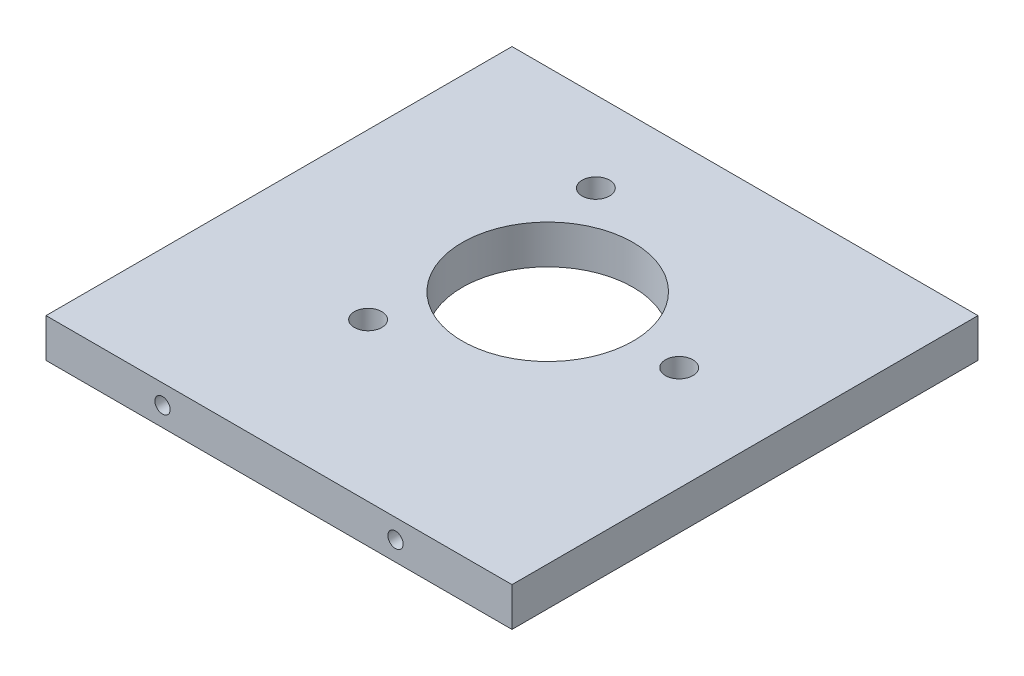
SolidWorks part; units mm, degrees
ref_plane "Front Plane" through (0, 0, 0) normal (0, 0, 1) x (1, 0, 0)
ref_plane "Top Plane" through (0, 0, 0) normal (0, 1, 0) x (1, 0, 0)
ref_plane "Right Plane" through (0, 0, 0) normal (1, 0, 0) x (0, 0, -1)
sketch "Sketch1" plane through (0, 0, 0) normal (0, 0, 1) x (1, 0, 0)
  line L0 (0, 3.175) -> (0, -3.175)
  line L1 (-38.1, 0) -> (38.1, 0) construction
  point P6 (0, 0)
  dimension "Width" = 76.2
  dimension "Thk" = 6.35
sketch "Sketch2" plane through (0, 0, 0) normal (1, 0, 0) x (0, 0, -1)
  line L0 (76.2, 0) -> (-76.2, 0)
  point P4 (0, 0)
  dimension "Length" = 152.4
sketch "Sketch3" plane through (0, 0, 0) normal (0, 0, 1) x (1, 0, 0)
  line L1 (38.1, 3.175) -> (-38.1, 3.175)
  line L2 (38.1, 3.175) -> (38.1, -3.175)
  line L3 (38.1, -3.175) -> (-38.1, -3.175)
  line L4 (-38.1, 3.175) -> (-38.1, -3.175)
  line L5 (38.1, 3.175) -> (-38.1, -3.175) construction
  line L6 (38.1, -3.175) -> (-38.1, 3.175) construction
  point P0 (0, 0)
extrude "Boss-Extrude1" add sketch "Sketch3" along normal up to vertex (76.2 mm away) and the other way up to vertex (76.2 mm away) up to point (0, 0, 76.2) other way up to point (0, 0, -76.2)
sketch "Sketch4" plane through (0, 3.175, 0) normal (0, 1, 0) x (1, 0, 0)
  point P1 (0, -1.15)
hole_wizard "M8 Clearance Hole1" [suppressed] positions "Sketch5" profile "Sketch6" hole size "M8" standard "ANSI Metric"
sketch "Sketch5" plane through (0, 3.175, 0) normal (0, 1, 0) x (1, 0, 0)
  point P8 (0, -1.15)
sketch "Sketch6" plane through (0, 3.175, 1.15) normal (1, 0, 0) x (0, 0, 1)
  line L0 (0, 0) -> (0, 6.35)
  line L1 (0, 6.35) -> (4.5, 6.35)
  line L2 (4.5, 6.35) -> (4.5, 0)
  line L5 (4.5, 0) -> (0, 0)
  line L11 (0, -6.35) -> (0, 107.95) construction
  dimension "Thru Hole Dia." = 9
  dimension "Thru Hole Depth" = 6.35
sketch "Sketch7" plane through (0, 3.175, 0) normal (0, 1, 0) x (1, 0, 0)
  point P0 (-8.2489, -5.9125)
  point P1 (0, -10.675)
  point P3 (8.2489, -5.9125)
  point P5 (8.2489, 3.6125)
  point P7 (0, 8.375)
  point P9 (-8.2489, 3.6125)
hole_wizard "CSK for M3 Flat Head Machine Screw1" [suppressed] positions "Sketch8" profile "Sketch10" countersink size "M3" standard "ANSI Metric"
sketch "Sketch8" plane through (0, 3.175, 0) normal (0, 1, 0) x (1, 0, 0)
  point P0 (-8.2489, -5.9125)
  point P3 (0, -10.675)
  point P6 (8.2489, -5.9125)
  point P9 (8.2489, 3.6125)
  point P12 (0, 8.375)
  point P15 (-8.2489, 3.6125)
sketch "Sketch10" plane through (-8.2489, -3.175, 5.9125) normal (1, 0, 0) x (0, 0, -1)
  line L0 (0, 0) -> (0, 6.35)
  line L1 (0, 6.35) -> (1.7, 6.35)
  line L2 (1.7, 6.35) -> (1.7, 1.45)
  line L3 (1.7, 1.45) -> (3.15, 0)
  line L5 (3.15, 0) -> (0, 0)
  line L6 (-1.7, 1.45) -> (-3.15, 0) construction
  line L11 (0, -6.35) -> (0, 107.95) construction
  dimension "Thru Hole Dia." = 3.4
  dimension "Thru Hole Depth" = 6.35
  dimension "Near C'Sink Dia." = 6.3
  dimension "Near C'Sink Angle" = 90
sketch "Sketch11" plane through (0, -3.175, 0) normal (0, -1, 0) x (1, 0, 0)
  circle A0 centre (-0.451, 31.8101) radius 13.97
  point P0 (-0.451, 31.8101)
  dimension "D1" = 27.94
extrude "Cut-Extrude1" cut sketch "Sketch11" against normal through all
sketch "Sketch12" plane through (0, -3.175, 0) normal (0, -1, 0) x (1, 0, 0)
  point P0 (-11.201, 13.1905)
  point P1 (21.049, 31.8101)
  point P3 (-11.201, 50.4296)
hole_wizard "CSK for M4 Flat Head Machine Screw1" positions "Sketch13" profile "Sketch14" countersink size "M4" standard "ANSI Metric" end condition through all
sketch "Sketch13" plane through (0, -3.175, 0) normal (0, -1, 0) x (-1, 0, 0)
  point P0 (11.201, -13.1905)
  point P3 (-21.049, -31.8101)
  point P6 (11.201, -50.4296)
sketch "Sketch14" plane through (-11.201, -3.175, 13.1905) normal (1, 0, 0) x (0, 0, -1)
  line L0 (0, 0) -> (0, 6.35)
  line L1 (0, 6.35) -> (2.25, 6.35)
  line L2 (2.25, 6.35) -> (2.25, 2.45)
  line L3 (2.25, 2.45) -> (4.7, 0)
  line L5 (4.7, 0) -> (0, 0)
  line L6 (-2.25, 2.45) -> (-4.7, 0) construction
  line L11 (0, -6.35) -> (0, 107.95) construction
  dimension "Thru Hole Dia." = 4.5
  dimension "Thru Hole Depth" = 6.35
  dimension "Near C'Sink Dia." = 9.4
  dimension "Near C'Sink Angle" = 90
sketch "Sketch15" plane through (0, -3.175, 0) normal (0, -1, 0) x (1, 0, 0)
  point P0 (-0.451, 31.8101)
hole_wizard "M16 Clearance Hole1" [suppressed] positions "Sketch18" profile "Sketch19" hole size "M16" standard "ANSI Metric"
sketch "Sketch18" plane through (0, -3.175, 0) normal (0, -1, 0) x (-1, 0, 0)
  point P0 (4.1552, -31.8101)
sketch "Sketch19" plane through (-4.1552, -3.175, 31.8101) normal (1, 0, 0) x (0, 0, -1)
  line L0 (0, 0) -> (0, 6.35)
  line L1 (0, 6.35) -> (8.75, 6.35)
  line L2 (8.75, 6.35) -> (8.75, 0)
  line L5 (8.75, 0) -> (0, 0)
  line L11 (0, -6.35) -> (0, 107.95) construction
  dimension "Thru Hole Dia." = 17.5
  dimension "Thru Hole Depth" = 6.35
sketch "Sketch20" plane through (0, -3.175, 0) normal (0, -1, 0) x (1, 0, 0)
  line L0 (-38.1, 76.2) -> (-38.1, -76.2) construction
  line L1 (38.1, -76.2) -> (-38.1, -76.2)
  line L2 (38.1, -76.2) -> (38.1, 0)
  line L3 (38.1, 0) -> (-38.1, 0)
  line L4 (-38.1, -76.2) -> (-38.1, 0)
  line L5 (-38.1, 76.2) -> (38.1, 76.2) construction
  dimension "D1" = 76.2
extrude "Cut-Extrude2" cut sketch "Sketch20" against normal through all
sketch "Sketch21" plane through (0, 3.175, 0) normal (0, 1, 0) x (1, 0, 0)
  circle A0 centre (0.6258, -38.1) radius 13.97
  point P0 (0.6258, -38.1)
  dimension "D1" = 27.94
extrude "Cut-Extrude3" [suppressed] cut sketch "Sketch21" against normal through all
sketch "Sketch22" plane through (0, 3.175, 0) normal (0, 1, 0) x (1, 0, 0)
  point P0 (0.6258, -59.6)
  point P1 (-17.9937, -27.35)
  point P3 (19.2454, -27.35)
hole_wizard "CSK for M4 Flat Head Machine Screw2" [suppressed] positions "Sketch23" profile "Sketch25" countersink size "M4" standard "ANSI Metric"
sketch "Sketch23" plane through (0, 3.175, 0) normal (0, 1, 0) x (1, 0, 0)
  point P0 (0.6258, -59.6)
  point P3 (19.2454, -27.35)
  point P6 (-17.9937, -27.35)
sketch "Sketch25" plane through (0.6258, 3.175, 59.6) normal (1, 0, 0) x (0, 0, 1)
  line L0 (0, 0) -> (0, 6.35)
  line L1 (0, 6.35) -> (2.25, 6.35)
  line L2 (2.25, 6.35) -> (2.25, 2.45)
  line L3 (2.25, 2.45) -> (4.7, 0)
  line L5 (4.7, 0) -> (0, 0)
  line L6 (-2.25, 2.45) -> (-4.7, 0) construction
  line L11 (0, -6.35) -> (0, 107.95) construction
  dimension "Thru Hole Dia." = 4.5
  dimension "Thru Hole Depth" = 6.35
  dimension "Near C'Sink Dia." = 9.4
  dimension "Near C'Sink Angle" = 90
sketch "Sketch26" [suppressed] plane through (0, 3.175, 0) normal (0, 1, 0) x (1, 0, 0)
  line L0 (38.1, -76.2) -> (38.1, 76.2) construction
  line L1 (-38.1, -76.2) -> (38.1, -76.2)
  line L2 (-38.1, -76.2) -> (-38.1, 25.4)
  line L3 (-38.1, 25.4) -> (38.1, 25.4)
  line L4 (38.1, -76.2) -> (38.1, 25.4)
  line L5 (38.1, 76.2) -> (-38.1, 76.2) construction
  dimension "D1" = 50.8
extrude "Cut-Extrude4" [suppressed] cut sketch "Sketch26" against normal through all contours L3 L4 L1 L2
sketch "Sketch27" [suppressed] plane through (-38.1, 0, 0) normal (-1, 0, 0) x (0, 0, 1)
  line L0 (-63.5, 0) -> (-38.1, 0) construction
  line L1 (-25.4, 3.175) -> (-76.2, 3.175) construction
  line L2 (-76.2, 3.175) -> (-76.2, -3.175) construction
  point P0 (-63.5, 0)
  point P1 (-38.1, 0)
  point P4 (-50.8, 0)
  point P7 (-50.8, 3.175)
  point P10 (-76.2, 0)
  dimension "D1" = 25.4
sketch "Sketch31" [suppressed] plane through (0, 3.175, 0) normal (0, 1, 0) x (1, 0, 0)
  line L0 (38.1, 76.2) -> (-38.1, 76.2) construction
  line L1 (38.1, 25.4) -> (5.08, 25.4)
  line L2 (38.1, 25.4) -> (38.1, 76.2)
  line L3 (38.1, 76.2) -> (5.08, 76.2)
  line L4 (5.08, 25.4) -> (5.08, 76.2)
  line L5 (-38.1, 25.4) -> (-38.1, 76.2) construction
  dimension "D1" = 43.18
extrude "Cut-Extrude5" [suppressed] cut sketch "Sketch31" against normal through all
hole_wizard "M3x0.5 Tapped Hole1" [suppressed] positions "Sketch28" profile "Sketch30" tap size "M3x0.5" standard "ANSI Metric"
sketch "Sketch28" [suppressed] plane through (-38.1, 0, 0) normal (-1, 0, 0) x (0, 0, 1)
  point P0 (-63.5, 0)
  point P3 (-38.1, 0)
cosmetic thread "Hole Thread1" [suppressed] parameters "D1"=4.0005, "D2"=3
cosmetic thread "Hole Thread2" [suppressed] parameters "D1"=4.0005, "D2"=3
sketch "Sketch30" plane through (-38.1, 0, -63.5) normal (0, 1, 0) x (0, 0, 1)
  line L0 (0, 0) -> (0, 6.35)
  line L1 (0, 6.35) -> (1.25, 5.5989)
  line L2 (1.25, 5.5989) -> (1.25, 0)
  line L5 (1.25, 0) -> (0, 0)
  line L10 (0, 6.35) -> (-1.25, 5.5989) construction
  line L11 (0, -6.35) -> (0, 107.95) construction
  dimension "Tap Drill Dia." = 2.5
  dimension "Tap Drill Depth" = 6.35
  dimension "Drill Angle" = 118
hole_wizard "M3x0.5 Tapped Hole2" [suppressed] positions "Sketch32" profile "Sketch33" tap size "M3x0.5" standard "ANSI Metric"
sketch "Sketch32" [suppressed] plane through (5.08, 0, 0) normal (1, 0, 0) x (0, 0, -1)
  point P0 (38.1, 0)
  point P3 (63.5, 0)
sketch "Sketch33" plane through (5.08, 0, -38.1) normal (0, 1, 0) x (0, 0, -1)
  line L0 (0, 0) -> (0, 12.7)
  line L1 (0, 12.7) -> (1.25, 11.9489)
  line L2 (1.25, 11.9489) -> (1.25, 0)
  line L5 (1.25, 0) -> (0, 0)
  line L10 (0, 12.7) -> (-1.25, 11.9489) construction
  line L11 (0, -6.35) -> (0, 107.95) construction
  dimension "Tap Drill Dia." = 2.5
  dimension "Tap Drill Depth" = 12.7
  dimension "Drill Angle" = 118
cosmetic thread "Hole Thread3" [suppressed] parameters "D1"=4.0005, "D2"=3
cosmetic thread "Hole Thread4" [suppressed] parameters "D1"=4.0005, "D2"=3
sketch "Sketch34" [suppressed] plane through (0, -3.175, 0) normal (0, -1, 0) x (1, 0, 0)
  point P0 (-12.7, 73.025)
  point P1 (12.7, 73.025)
  point P3 (-12.7, 3.175)
  point P5 (12.7, 3.175)
hole_wizard "CSK for M3 Flat Head Machine Screw3" [suppressed] positions "Sketch35" profile "Sketch36" countersink size "M3" standard "ANSI Metric"
sketch "Sketch35" [suppressed] plane through (0, -3.175, 0) normal (0, -1, 0) x (-1, 0, 0)
  point P0 (12.7, -73.025)
  point P3 (-12.7, -73.025)
  point P6 (12.7, -3.175)
  point P9 (-12.7, -3.175)
sketch "Sketch36" plane through (-12.7, -3.175, 73.025) normal (1, 0, 0) x (0, 0, -1)
  line L0 (0, 0) -> (0, 6.35)
  line L1 (0, 6.35) -> (1.7, 6.35)
  line L2 (1.7, 6.35) -> (1.7, 1.45)
  line L3 (1.7, 1.45) -> (3.15, 0)
  line L5 (3.15, 0) -> (0, 0)
  line L6 (-1.7, 1.45) -> (-3.15, 0) construction
  line L11 (0, -6.35) -> (0, 107.95) construction
  dimension "Thru Hole Dia." = 3.4
  dimension "Thru Hole Depth" = 6.35
  dimension "Near C'Sink Dia." = 6.3
  dimension "Near C'Sink Angle" = 90
sketch "Sketch37" plane through (0, 0, 76.2) normal (0, 0, 1) x (1, 0, 0)
  line L0 (19.05, 0) -> (-19.05, 0) construction
  line L1 (38.1, -3.175) -> (38.1, 3.175) construction
  line L2 (-38.1, -3.175) -> (38.1, -3.175) construction
  point P4 (38.1, 0)
  point P7 (0, -3.175)
  point P8 (0, 0)
  point P10 (19.05, 0)
  point P11 (-19.05, 0)
  dimension "D1" = 38.1
hole_wizard "M3x0.5 Tapped Hole3" positions "Sketch38" profile "Sketch40" tap size "M3x0.5" standard "ANSI Metric"
sketch "Sketch38" plane through (0, 0, 76.2) normal (0, 0, 1) x (1, 0, 0)
  point P0 (19.05, 0)
  point P3 (-19.05, 0)
sketch "Sketch40" plane through (19.05, 0, 76.2) normal (1, 0, 0) x (0, -1, 0)
  line L0 (0, 0) -> (0, 12.7)
  line L1 (0, 12.7) -> (1.25, 11.9489)
  line L2 (1.25, 11.9489) -> (1.25, 0)
  line L5 (1.25, 0) -> (0, 0)
  line L10 (0, 12.7) -> (-1.25, 11.9489) construction
  line L11 (0, -6.35) -> (0, 107.95) construction
  dimension "Tap Drill Dia." = 2.5
  dimension "Tap Drill Depth" = 12.7
  dimension "Drill Angle" = 118
cosmetic thread "Hole Thread5" parameters "D1"=5.9995, "D2"=3
cosmetic thread "Hole Thread6" parameters "D1"=5.9995, "D2"=3
sketch "Sketch41" [suppressed] plane through (0, -3.175, 0) normal (0, -1, 0) x (1, 0, 0)
  point P0 (19.05, -21.025)
  point P1 (19.05, -73.025)
  point P3 (-19.05, -73.025)
  point P5 (-19.05, -21.025)
hole_wizard "CSK for M3 Flat Head Machine Screw2" [suppressed] positions "Sketch42" profile "Sketch44" countersink size "M3" standard "ANSI Metric"
sketch "Sketch42" [suppressed] plane through (0, -3.175, 0) normal (0, -1, 0) x (-1, 0, 0)
  point P0 (-19.05, 21.025)
  point P3 (19.05, 21.025)
  point P6 (-19.05, 73.025)
  point P9 (19.05, 73.025)
sketch "Sketch44" plane through (19.05, -3.175, -21.025) normal (1, 0, 0) x (0, 0, -1)
  line L0 (0, 0) -> (0, 6.35)
  line L1 (0, 6.35) -> (1.7, 6.35)
  line L2 (1.7, 6.35) -> (1.7, 1.45)
  line L3 (1.7, 1.45) -> (3.15, 0)
  line L5 (3.15, 0) -> (0, 0)
  line L6 (-1.7, 1.45) -> (-3.15, 0) construction
  line L11 (0, -6.35) -> (0, 107.95) construction
  dimension "Thru Hole Dia." = 3.4
  dimension "Thru Hole Depth" = 6.35
  dimension "Near C'Sink Dia." = 6.3
  dimension "Near C'Sink Angle" = 90
